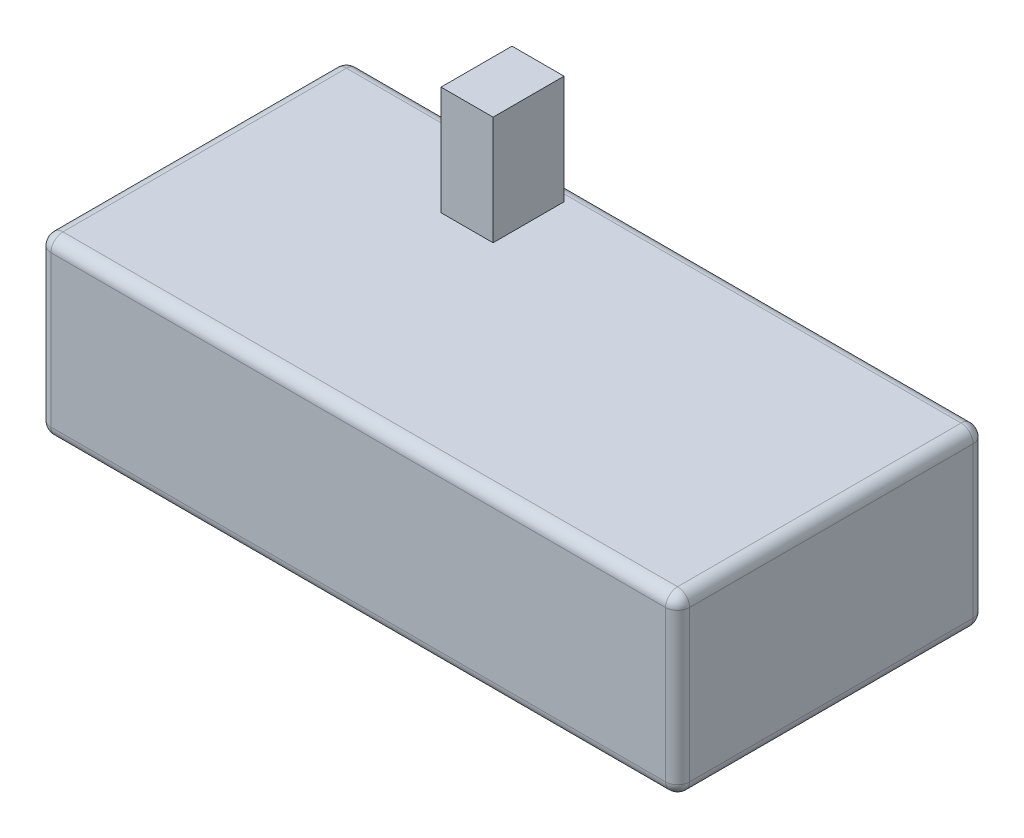
SolidWorks part; units mm, degrees
ref_plane "Front Plane" through (0, 0, 0) normal (0, 0, 1) x (1, 0, 0)
ref_plane "Top Plane" through (0, 0, 0) normal (0, 1, 0) x (1, 0, 0)
ref_plane "Right Plane" through (0, 0, 0) normal (1, 0, 0) x (0, 0, -1)
sketch "Sketch1" plane through (0, 0, 0) normal (0, 1, 0) x (1, 0, 0)
  line L1 (0, 0) -> (135, 0)
  line L2 (0, 0) -> (0, -65)
  line L3 (0, -65) -> (135, -65)
  line L4 (135, 0) -> (135, -65)
  dimension "D1" = 65
  dimension "D2" = 135
extrude "Boss-Extrude1" add sketch "Sketch1" along normal blind 37
fillet "Fillet1" radius 2.54 12 edges at (67.5, 0, 0) (0, 18.5, 0) (0, 0, 32.5) (0, 18.5, 65) (67.5, 0, 65) (135, 18.5, 65) (135, 18.5, 0) (135, 0, 32.5) (67.5, 37, 0) (135, 37, 32.5) (67.5, 37, 65) (0, 37, 32.5)
sketch "Sketch2" plane through (0, 37, 0) normal (0, 1, 0) x (1, 0, 0)
  line L0 (0, -19) -> (50, -19) construction
  line L1 (0, -62.46) -> (0, -2.54) construction
  line L2 (2.54, 0) -> (132.46, 0) construction
  line L4 (50, -19) -> (39, -19)
  line L5 (50, -19) -> (50, -4)
  line L6 (50, -4) -> (39, -4)
  line L7 (39, -19) -> (39, -4)
  dimension "D1" = 50
  dimension "D2" = 19
  dimension "D3" = 15
  dimension "D4" = 11
extrude "Boss-Extrude2" add sketch "Sketch2" along normal blind 23
sketch "Sketch3" plane through (0, 0, 0) normal (0, 0, -1) x (-1, 0, 0)
  line L0 (-66, 0) -> (-66, 12) construction
  line L1 (-2.54, 0) -> (-132.46, 0) construction
  line L2 (0, 34.46) -> (0, 2.54) construction
  line L4 (-66, 12) -> (-53, 12)
  line L5 (-66, 12) -> (-66, 8)
  line L6 (-66, 8) -> (-53, 8)
  line L7 (-53, 12) -> (-53, 8)
  dimension "D1" = 12
  dimension "D2" = 66
  dimension "D3" = 13
  dimension "D4" = 4
extrude "Boss-Extrude3" add sketch "Sketch3" along normal blind 10
sketch "Sketch4" plane through (0, 12, 0) normal (0, 1, 0) x (1, 0, 0)
  line L0 (66, 8) -> (53, 8) construction
  line L1 (66, 10) -> (66, 0) construction
  line L2 (53, 10) -> (53, 0) construction
  line L3 (53, 10) -> (66, 10) construction
  line L4 (57, 0) -> (57, 10) construction
  line L5 (53, 0) -> (66, 0) construction
  line L6 (62, 0) -> (62, 10) construction
  line L7 (62, 3) -> (57, 3)
  line L8 (62, 8) -> (57, 8)
  line L9 (57, 8) -> (57, 3)
  line L10 (62, 3) -> (62, 8)
  dimension "D1" = 2
  dimension "D2" = 4
  dimension "D3" = 4
  dimension "D4" = 5
extrude "Cut-Extrude1" cut sketch "Sketch4" against normal through all
